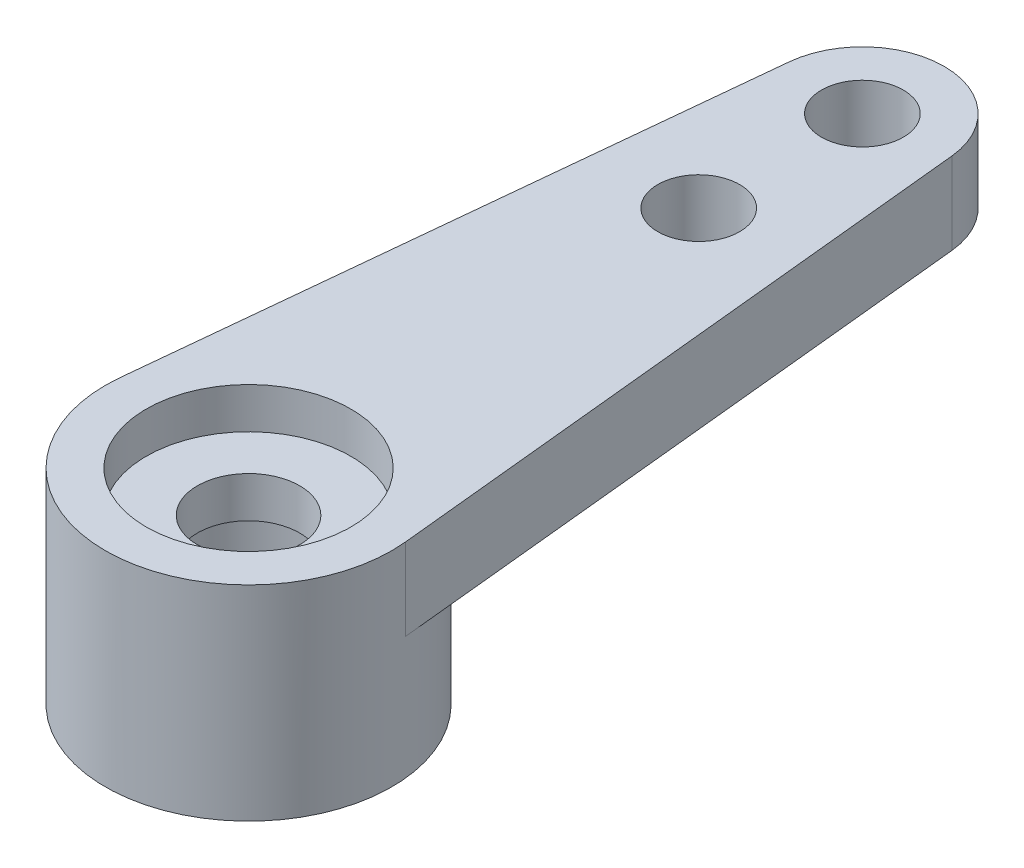
SolidWorks part; units mm, degrees
material "氧化铝"
ref_plane "前视基准面" through (0, 0, 0) normal (0, 0, 1) x (1, 0, 0)
ref_plane "上视基准面" through (0, 0, 0) normal (0, 1, 0) x (1, 0, 0)
ref_plane "右视基准面" through (0, 0, 0) normal (1, 0, 0) x (0, 0, -1)
other "Configuration Table"
sketch "草图1" plane through (0, 0, 0) normal (0, 1, 0) x (1, 0, 0)
  line L0 (-3.4825, 0.35) -> (-1.99, 15.2)
  line L1 (1.99, 15.2) -> (3.4825, 0.35)
  arc A0 (-3.4825, 0.35) -> (3.4825, 0.35) centre (0, 0) ccw
  arc A1 (-1.99, 15.2) -> (1.99, 15.2) centre (0, 15) cw
  circle A2 centre (0, 15) radius 1
  circle A3 centre (0, 11) radius 1
  circle A4 centre (0, 0) radius 1.25
  dimension "D1" = 3.5
  dimension "D2" = 2
  dimension "D3" = 2
  dimension "D4" = 2
  dimension "D7" = 2.5
  dimension "D5" = 4
  dimension "D6" = 11
extrude "凸台-拉伸1" add sketch "草图1" along normal blind 2
sketch "草图2" plane through (0, 0, 0) normal (0, -1, 0) x (1, 0, 0)
  circle A0 centre (0, 0) radius 3.5
  arc A1 (3.4825, -0.35) -> (-3.4825, -0.35) centre (0, 0) ccw construction
  circle A2 centre (0, 0) radius 2
  dimension "D1" = 4
extrude "凸台-拉伸2" add sketch "草图2" along normal blind 3
sketch "草图3" plane through (0, 2, 0) normal (0, 1, 0) x (1, 0, 0)
  circle A0 centre (0, 0) radius 2.5
  dimension "D1" = 5
extrude "切除-拉伸1" cut sketch "草图3" against normal blind 1
